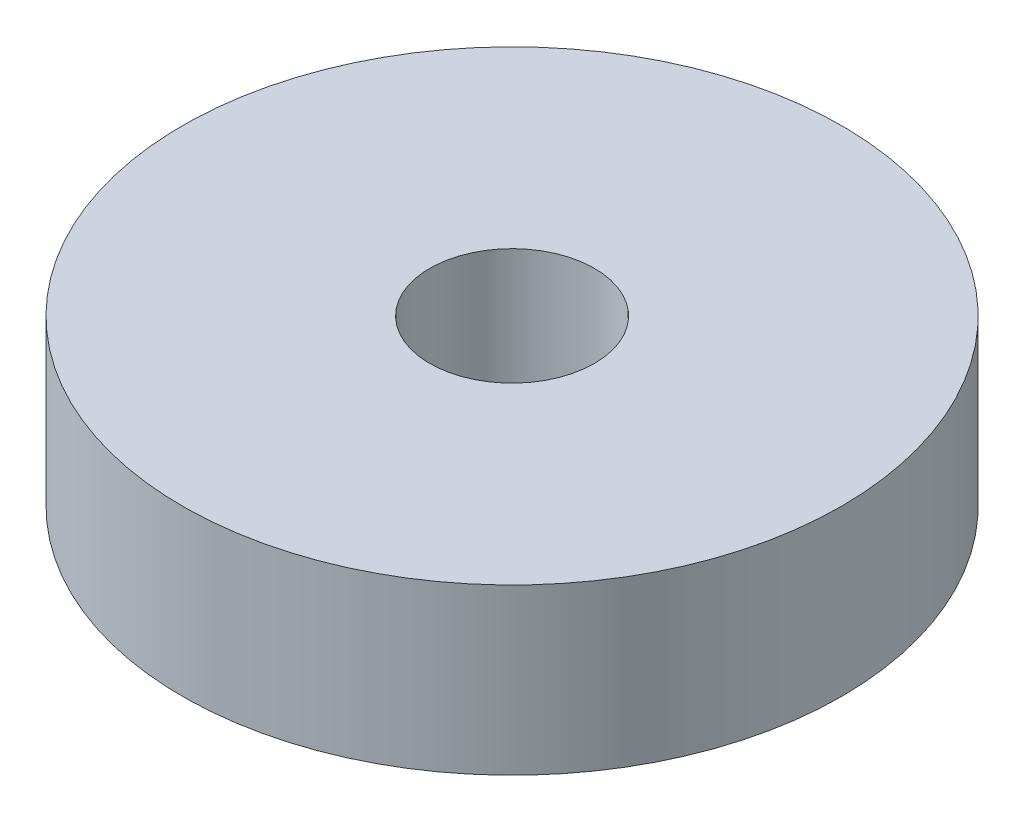
SolidWorks part; units mm, degrees
material "三聚氰胺甲醛树脂"
ref_plane "前视基准面" through (0, 0, 0) normal (0, 0, 1) x (1, 0, 0)
ref_plane "上视基准面" through (0, 0, 0) normal (0, 1, 0) x (1, 0, 0)
ref_plane "右视基准面" through (0, 0, 0) normal (1, 0, 0) x (0, 0, -1)
sketch "草图1" plane through (0, 0, 0) normal (0, 0, 1) x (1, 0, 0)
  line L0 (0, -110.3035) -> (0, 5404.8728) construction
  line L1 (-110.3035, 0) -> (5404.8728, 0) construction
  line L2 (1.5, 1.5) -> (1.5, -1.5)
  line L3 (1.5, 1.5) -> (6, 1.5)
  line L4 (1.5, -1.5) -> (6, -1.5)
  line L5 (6, 1.5) -> (6, -1.5)
  dimension "D1" = 12
  dimension "D2" = 1.5
  dimension "D3" = 1.5
  dimension "D4" = 3
revolve "旋转1" add sketch "草图1" angle 360 about L0
